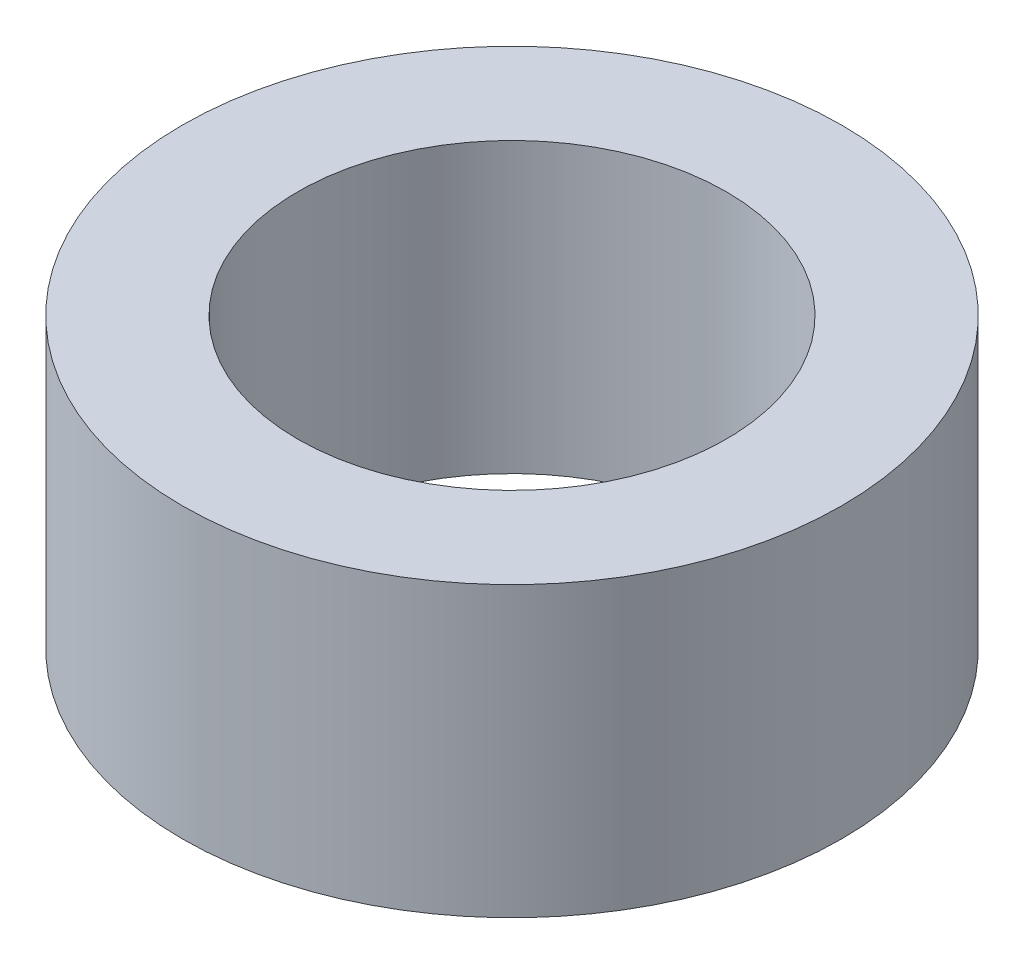
SolidWorks part; units mm, degrees
ref_plane "正面" through (0, 0, 0) normal (0, 0, 1) x (1, 0, 0)
ref_plane "平面" through (0, 0, 0) normal (0, 1, 0) x (1, 0, 0)
ref_plane "右側面" through (0, 0, 0) normal (1, 0, 0) x (0, 0, -1)
sketch "ｽｹｯﾁ1" plane through (0, 0, 0) normal (0, 1, 0) x (1, 0, 0)
  circle A0 centre (0, 0) radius 2.6
  circle A1 centre (0, 0) radius 4
  dimension "D1" = 5.2
  dimension "D2" = 8
extrude "ﾎﾞｽ - 押し出し1" add sketch "ｽｹｯﾁ1" along normal blind 3.5
